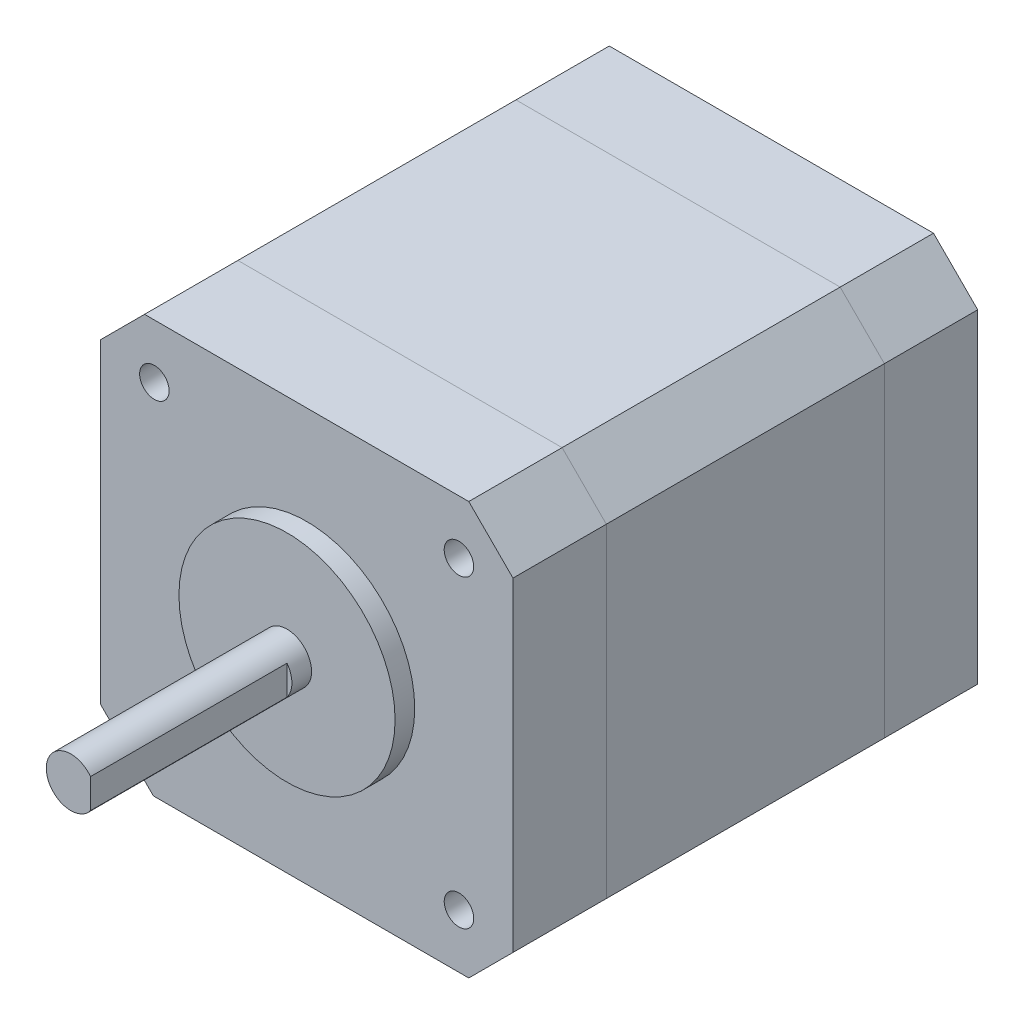
SolidWorks part; units mm, degrees
ref_plane "Front Plane" through (0, 0, 0) normal (0, 0, 1) x (1, 0, 0)
ref_plane "Top Plane" through (0, 0, 0) normal (0, 1, 0) x (1, 0, 0)
ref_plane "Right Plane" through (0, 0, 0) normal (1, 0, 0) x (0, 0, -1)
sketch "Sketch1" plane through (0, 0, 0) normal (0, 0, 1) x (1, 0, 0)
  line L0 (-21, 16.5) -> (-16.5, 21)
  line L1 (-16.5, 21) -> (16.5, 21)
  line L2 (-21, 16.5) -> (-21, -15.6)
  line L3 (-15.6, -21) -> (16.5, -21)
  line L4 (21, 16.5) -> (21, -16.5)
  line L5 (-21, 21) -> (21, -21) construction
  line L6 (-21, -21) -> (21, 21) construction
  line L7 (16.5, 21) -> (21, 16.5)
  line L8 (16.5, -21) -> (21, -16.5)
  line L9 (-21, -15.6) -> (-15.6, -21)
  point P0 (0, 0)
  dimension "D1" = 42
  dimension "D2" = 42
extrude "Boss-Extrude1" add sketch "Sketch1" along normal blind 9.5
ref_plane "Plane2" through (0, 0, 47.3) normal (0, 0, -1) x (-1, 0, 0)
sketch "Sketch8" plane through (0, 0, 47.3) normal (0, 0, -1) x (-1, 0, 0)
  line L8 (21, 16.5) -> (16.5, 21)
  line L9 (16.5, 21) -> (-16.5, 21)
  line L10 (-16.5, 21) -> (-21, 16.5)
  line L11 (-21, 16.5) -> (-21, -16.5)
  line L12 (-21, -16.5) -> (-16.5, -21)
  line L13 (-16.5, -21) -> (15.6, -21)
  line L14 (15.6, -21) -> (21, -15.6)
  line L15 (21, -15.6) -> (21, 16.5)
  line L16 (21, 16.5) -> (16.5, 21)
  line L17 (16.5, 21) -> (-16.5, 21)
  line L18 (-16.5, 21) -> (-21, 16.5)
  line L19 (-21, 16.5) -> (-21, -16.5)
  line L20 (-21, -16.5) -> (-16.5, -21)
  line L21 (-16.5, -21) -> (15.6, -21)
  line L22 (15.6, -21) -> (21, -15.6)
  line L23 (21, -15.6) -> (21, 16.5)
  dimension "D1" = 0
extrude "Boss-Extrude7" add sketch "Sketch8" along normal blind 9.5 separate body
sketch "草图6" plane through (0, 0, 9.5) normal (0, 0, 1) x (1, 0, 0)
  line L8 (16.5, 21) -> (-16.5, 21)
  line L9 (-16.5, 21) -> (-21, 16.5)
  line L10 (-21, 16.5) -> (-21, -15.6)
  line L11 (-21, -15.6) -> (-15.6, -21)
  line L12 (-15.6, -21) -> (16.5, -21)
  line L13 (16.5, -21) -> (21, -16.5)
  line L14 (21, -16.5) -> (21, 16.5)
  line L15 (21, 16.5) -> (16.5, 21)
  line L16 (16.5, 21) -> (-16.5, 21)
  line L17 (-16.5, 21) -> (-21, 16.5)
  line L18 (-21, 16.5) -> (-21, -15.6)
  line L19 (-21, -15.6) -> (-15.6, -21)
  line L20 (-15.6, -21) -> (16.5, -21)
  line L21 (16.5, -21) -> (21, -16.5)
  line L22 (21, -16.5) -> (21, 16.5)
  line L23 (21, 16.5) -> (16.5, 21)
  dimension "D1" = 0
extrude "凸台-拉伸5" add sketch "草图6" along normal blind 28.3 separate body
sketch "Sketch11" plane through (0, 0, 47.3) normal (0, 0, 1) x (1, 0, 0)
  circle A0 centre (0, 0) radius 11
  dimension "D1" = 22
extrude "Boss-Extrude9" add sketch "Sketch11" along normal blind 2 separate body
sketch "Sketch10" plane through (0, 0, 47.3) normal (0, 0, 1) x (1, 0, 0)
  circle A0 centre (-15.5, 15.5) radius 1.5
  circle A1 centre (15.5, 15.5) radius 1.5
  circle A2 centre (15.5, -15.5) radius 1.5
  circle A3 centre (-15.5, -15.5) radius 1.5
  dimension "D5" = 3
  dimension "D1" = 31
  dimension "D2" = 15.5
  dimension "D3" = 31
  dimension "D4" = 15.5
extrude "Cut-Extrude3" cut sketch "Sketch10" against normal blind 5.5
sketch "Sketch12" plane through (0, 0, 49.3) normal (0, 0, 1) x (1, 0, 0)
  circle A0 centre (0, 0) radius 2.5
  dimension "D1" = 5
extrude "Boss-Extrude10" add sketch "Sketch12" along normal blind 22 separate body
sketch "Sketch14" plane through (0, 0, 0) normal (0, 0, -1) x (-1, 0, 0)
  circle A1 centre (15.5, -15.5) radius 1.5
  circle A2 centre (15.5, -15.5) radius 1.5
  circle A3 centre (-15.5, -15.5) radius 1.5
  circle A4 centre (-15.5, -15.5) radius 1.5
  circle A5 centre (-15.5, 15.5) radius 1.5
  circle A6 centre (-15.5, 15.5) radius 1.5
  circle A7 centre (15.5, 15.5) radius 1.5
  circle A8 centre (15.5, 15.5) radius 1.5
  dimension "D1" = 0
  dimension "D2" = 0
  dimension "D3" = 0
  dimension "D4" = 0
extrude "Cut-Extrude5" cut sketch "Sketch14" against normal blind 5.5
sketch "Sketch16" plane through (0, 0, 0) normal (0, 0, -1) x (-1, 0, 0)
  circle A0 centre (0, 0) radius 2.5 construction
  circle A1 centre (0, 0) radius 4
  dimension "D1" = 5
  dimension "D2" = 8
extrude "Cut-Extrude6" cut sketch "Sketch16" against normal blind 2
sketch "Sketch17" plane through (0, 0, 2) normal (0, 0, -1) x (-1, 0, 0)
  circle A0 centre (0, 0) radius 2.5
  dimension "D1" = 5
extrude "Boss-Extrude11" add sketch "Sketch17" along normal blind 1 separate body
sketch "Sketch18" plane through (0, 0, 0) normal (0, 0, -1) x (-1, 0, 0)
  circle A0 centre (15.5, -15.5) radius 2.75
  circle A1 centre (-15.5, -15.5) radius 2.75
  circle A2 centre (-15.5, 15.5) radius 2.75
  circle A3 centre (15.5, 15.5) radius 2.75
  point P12 (0, 0)
  dimension "D1" = 5.5
  dimension "D2" = 4
extrude "Cut-Extrude7" cut sketch "Sketch18" against normal blind 1
ref_plane "基准面1" through (0, -21, 0) normal (0, -1, 0) x (-1, 0, 0)
sketch "草图3" plane through (0, -21, 0) normal (0, -1, 0) x (-1, 0, 0)
  line L0 (15.6, 0) -> (-16.5, 0) construction
  line L1 (-11, 0) -> (11, 0)
  line L2 (-11, 0) -> (-11, -7.5)
  line L3 (-11, -7.5) -> (11, -7.5)
  line L4 (11, 0) -> (11, -7.5)
  point P6 (0, -7.5)
  dimension "D1" = 22
  dimension "D2" = 7.5
extrude "凸台-拉伸4" add sketch "草图3" along normal blind 3 separate body
sketch "草图5" plane through (0, 0, 71.3) normal (0, 0, 1) x (1, 0, 0)
  line L0 (2, 0.6433) -> (2, -998.5) construction
  line L2 (2, 1.5) -> (2, -1.5)
  circle A0 centre (0, 0) radius 2.5 construction
  circle A3 centre (0, 0) radius 2.5
  arc A4 (2, -1.5) -> (2, 1.5) centre (0, 0) ccw
  dimension "D1" = 2
  dimension "D2" = 0
extrude "切除-拉伸1" cut sketch "草图5" against normal blind 20
